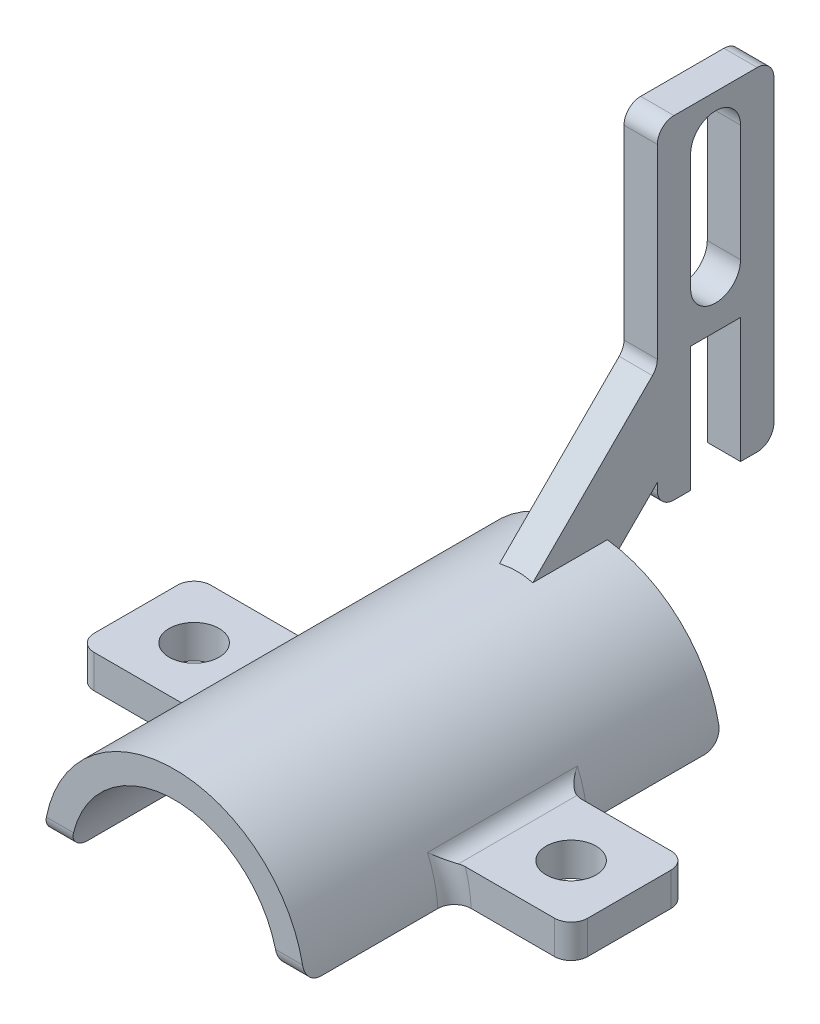
SolidWorks part; units mm, degrees
ref_plane "Front Plane" through (0, 0, 0) normal (0, 0, 1) x (1, 0, 0)
ref_plane "Top Plane" through (0, 0, 0) normal (0, 1, 0) x (1, 0, 0)
ref_plane "Right Plane" through (0, 0, 0) normal (1, 0, 0) x (0, 0, -1)
sketch "Sketch1" plane through (0, 0, 0) normal (0, 0, 1) x (1, 0, 0)
  line L0 (-7.8215, 0.5) -> (-6.23, 0.5)
  line L1 (6.23, 0.5) -> (7.8215, 0.5)
  arc A0 (6.23, 0.5) -> (-6.23, 0.5) centre (0, 0) ccw
  arc A1 (7.8215, 0.5) -> (-7.8215, 0.5) centre (0, 0) ccw
  dimension "D1" = 12.5
  dimension "D2" = 15.675
  dimension "D3" = 0.5
extrude "Boss-Extrude1" add sketch "Sketch1" along normal mid plane 25
sketch "Sketch4" plane through (0, 0, 0) normal (0, 1, 0) x (1, 0, 0)
  line L0 (14.8215, -12.4975) -> (14.8215, 12.6061) construction
  line L1 (7.8215, -12.5) -> (7.8215, 12.5) construction
  dimension "D1" = 7
ref_plane "Plane1" through (14.8215, 0, 0) normal (1, 0, 0) x (0, 0, -1)
sketch "Sketch5" plane through (14.8215, 0, 0) normal (1, 0, 0) x (0, 0, -1)
  line L0 (-12.5, 0.5) -> (12.5, 0.5) construction
  line L1 (-3.5, 0.5) -> (3.5, 0.5)
  line L2 (-3.5, 0.5) -> (-3.5, 2.5)
  line L3 (-3.5, 2.5) -> (3.5, 2.5)
  line L4 (3.5, 0.5) -> (3.5, 2.5)
  point P6 (0, 0.5)
  dimension "D1" = 2
  dimension "D2" = 7
extrude "Boss-Extrude3" add sketch "Sketch5" against normal up to surface (7 mm away)
sketch "Sketch6" plane through (0, 2.5, 0) normal (0, 1, 0) x (1, 0, 0)
  line L0 (7.8215, -3.5) -> (7.8215, 3.5) construction
  line L1 (7.8215, -3.5) -> (14.8215, 3.5) construction
  circle A0 centre (11.3215, 0) radius 1.5
  dimension "D1" = 3
extrude "Cut-Extrude2" cut sketch "Sketch6" against normal up to surface (2 mm away) up to face at (9.1736, 0.5, 0)
fillet "Fillet2" radius 1 5 edges at (7.6901, 1.5128, -3.5) (7.4281, 2.5, 0) (7.6901, 1.5128, 3.5) (14.8215, 1.5, -3.5) (14.8215, 1.5, 3.5)
mirror "Mirror2" about plane through (0, 0, 0) normal (1, 0, 0) of "Fillet2", "Cut-Extrude2", "Boss-Extrude3"
sketch "Sketch8" plane through (0, 0, 0) normal (1, 0, 0) x (0, 0, -1)
  line L1 (12.5, 6.25) -> (15.5, 9.25)
  line L15 (15.5, 15.25) -> (6.5, 6.25)
  line L16 (12.5, 6.25) -> (-12.5, 6.25) construction
  line L17 (6.5, 6.25) -> (12.5, 6.25)
  line L18 (15.5, 15.25) -> (15.5, 27.8375)
  line L19 (12.5, 0.5) -> (12.5, 7.8375) construction
  line L20 (15.5, 27.8375) -> (22.5, 27.8375)
  line L21 (22.5, 27.8375) -> (22.5, 7.8375)
  line L22 (22.5, 7.8375) -> (15.5, 7.8375)
  line L23 (15.5, 7.8375) -> (15.5, 9.25)
  dimension "D1" = 3
  dimension "D2" = 3
  dimension "D3" = 7
  dimension "D4" = 6
  dimension "D5" = 20
extrude "Boss-Extrude4" add sketch "Sketch8" along normal mid plane 2
sketch "Sketch11" plane through (1, 0, 0) normal (1, 0, 0) x (0, 0, -1)
  line L0 (19, 25.3375) -> (19, 18.3375) construction
  line L1 (20.5, 25.3375) -> (20.5, 18.3375)
  line L2 (17.5, 25.3375) -> (17.5, 18.3375)
  line L3 (22.5, 27.8375) -> (15.5, 27.8375) construction
  line L4 (15.5, 7.8375) -> (22.5, 7.8375) construction
  line L5 (17.5, 7.8375) -> (20.5, 7.8375)
  line L6 (17.5, 7.8375) -> (17.5, 15.3375)
  line L7 (17.5, 15.3375) -> (20.5, 15.3375)
  line L8 (20.5, 7.8375) -> (20.5, 15.3375)
  arc A0 (20.5, 25.3375) -> (17.5, 25.3375) centre (19, 25.3375) ccw
  arc A1 (17.5, 18.3375) -> (20.5, 18.3375) centre (19, 18.3375) ccw
  point P2 (19, 21.8375)
  point P8 (19, 26.8375)
  point P12 (19, 27.8375)
  point P14 (19, 16.8375)
  dimension "D1" = 3
  dimension "D2" = 1
  dimension "D3" = 10
  dimension "D4" = 1.5
extrude "Cut-Extrude4" cut sketch "Sketch11" against normal through all
fillet "Fillet3" radius 1 9 edges at (7.0258, 0.5, -12.5) (-7.0258, 0.5, -12.5) (-7.0258, 0.5, 12.5) (7.0258, 0.5, 12.5) (0, 27.8375, -15.5) (0, 27.8375, -22.5) (0, 7.8375, -15.5) (0, 7.8375, -22.5) (0, 15.25, -15.5)
